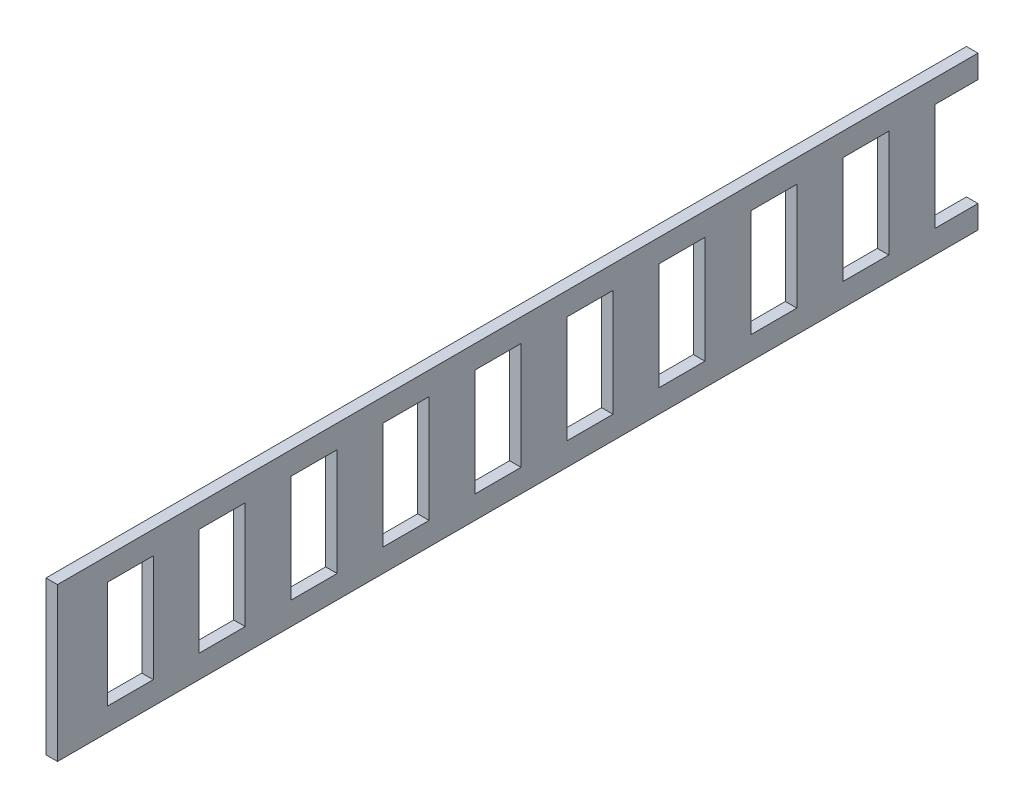
SolidWorks part; units mm, degrees
ref_plane "Front Plane" through (0, 0, 0) normal (0, 0, 1) x (1, 0, 0)
ref_plane "Top Plane" through (0, 0, 0) normal (0, 1, 0) x (1, 0, 0)
ref_plane "Right Plane" through (0, 0, 0) normal (1, 0, 0) x (0, 0, -1)
sketch "Sketch1" plane through (0, 0, 0) normal (1, 0, 0) x (0, 0, -1)
  line L1 (-600.7, 0) -> (600.7, 0)
  line L2 (-600.7, 0) -> (-600.7, 200)
  line L3 (-600.7, 200) -> (600.7, 200)
  line L4 (600.7, 0) -> (600.7, 30)
  line L5 (-535.7, 170) -> (-475.7, 170)
  line L6 (-535.7, 170) -> (-535.7, 30)
  line L7 (-535.7, 30) -> (-475.7, 30)
  line L8 (-475.7, 170) -> (-475.7, 30)
  line L52 (-535.7, 170) -> (-475.7, 170) construction
  line L53 (-415.7, 170) -> (-415.7, 30)
  line L54 (-415.7, 170) -> (-355.7, 170)
  line L55 (-355.7, 170) -> (-355.7, 30)
  line L56 (-415.7, 30) -> (-355.7, 30)
  line L57 (-295.7, 170) -> (-295.7, 30)
  line L58 (-295.7, 170) -> (-235.7, 170)
  line L59 (-235.7, 170) -> (-235.7, 30)
  line L60 (-295.7, 30) -> (-235.7, 30)
  line L61 (-175.7, 170) -> (-175.7, 30)
  line L62 (-175.7, 170) -> (-115.7, 170)
  line L63 (-115.7, 170) -> (-115.7, 30)
  line L64 (-175.7, 30) -> (-115.7, 30)
  line L65 (-55.7, 170) -> (-55.7, 30)
  line L66 (-55.7, 170) -> (4.3, 170)
  line L67 (4.3, 170) -> (4.3, 30)
  line L68 (-55.7, 30) -> (4.3, 30)
  line L69 (64.3, 170) -> (64.3, 30)
  line L70 (64.3, 170) -> (124.3, 170)
  line L71 (124.3, 170) -> (124.3, 30)
  line L72 (64.3, 30) -> (124.3, 30)
  line L73 (184.3, 170) -> (184.3, 30)
  line L74 (184.3, 170) -> (244.3, 170)
  line L75 (244.3, 170) -> (244.3, 30)
  line L76 (184.3, 30) -> (244.3, 30)
  line L77 (304.3, 170) -> (304.3, 30)
  line L78 (304.3, 170) -> (364.3, 170)
  line L79 (364.3, 170) -> (364.3, 30)
  line L80 (304.3, 30) -> (364.3, 30)
  line L81 (424.3, 170) -> (424.3, 30)
  line L82 (424.3, 170) -> (484.3, 170)
  line L83 (484.3, 170) -> (484.3, 30)
  line L84 (424.3, 30) -> (484.3, 30)
  line L85 (544.3, 170) -> (544.3, 30)
  line L86 (544.3, 170) -> (600.7, 170)
  line L88 (544.3, 30) -> (600.7, 30)
  line L89 (-535.7, 170) -> (-415.7, 170) construction
  line L90 (604.3, 170) -> (604.3, 30) [skipped]
  line L91 (600.7, 170) -> (600.7, 200)
  point P4 (0, 0)
  point P10 (-505.7, 170)
  dimension "D1" = 1201.4
  dimension "D2" = 200
  dimension "D3" = 30
  dimension "D4" = 30
  dimension "D5" = 65
  dimension "D6" = 60
  dimension "D8" = 120
  dimension "D7" = 10
extrude "Boss-Extrude1" add sketch "Sketch1" along normal blind 15
